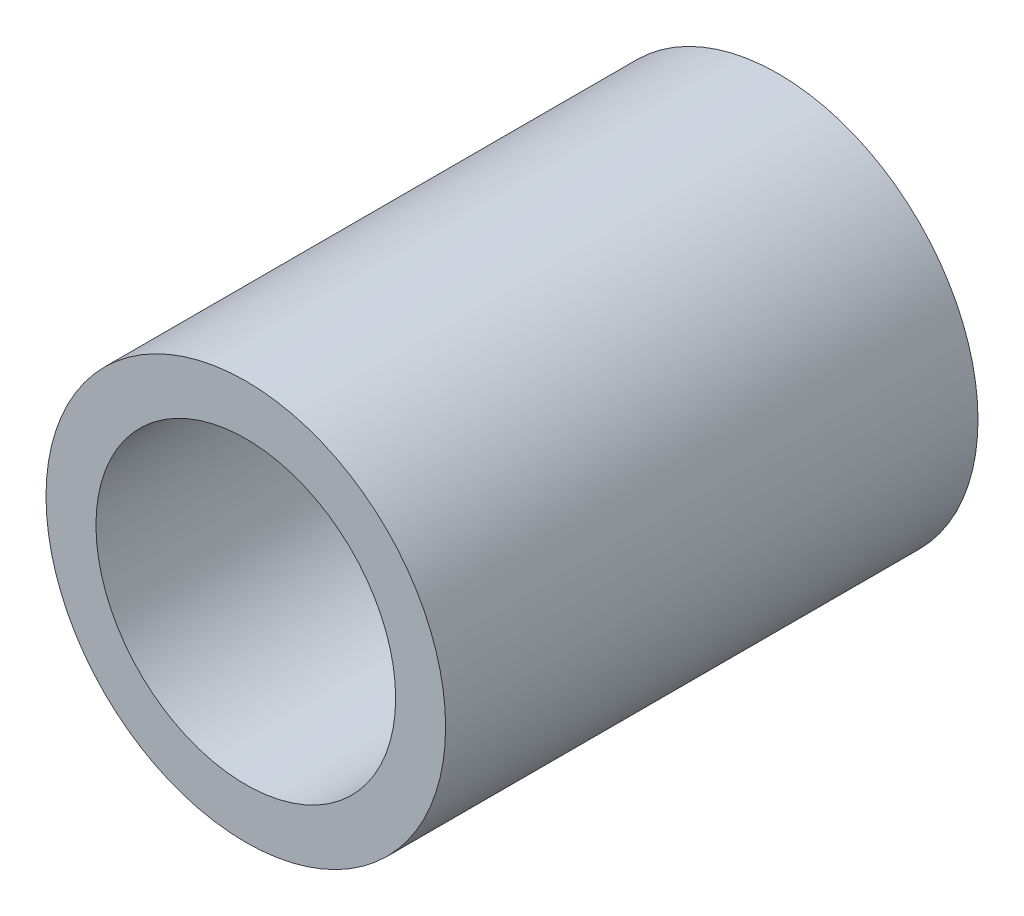
SolidWorks part; units mm, degrees
material "6061-T6 (SS)"
ref_plane "Front Plane" through (0, 0, 0) normal (0, 0, 1) x (1, 0, 0)
ref_plane "Top Plane" through (0, 0, 0) normal (0, 1, 0) x (1, 0, 0)
ref_plane "Right Plane" through (0, 0, 0) normal (1, 0, 0) x (0, 0, -1)
sketch "Sketch1" plane through (0, 0, 0) normal (0, 0, 1) x (1, 0, 0)
  circle A0 centre (0, 0) radius 9.525
  circle A1 centre (0, 0) radius 7.1437
  dimension "D1" = 14.2875
  dimension "D2" = 19.05
extrude "Boss-Extrude1" add sketch "Sketch1" along normal blind 25.3813
